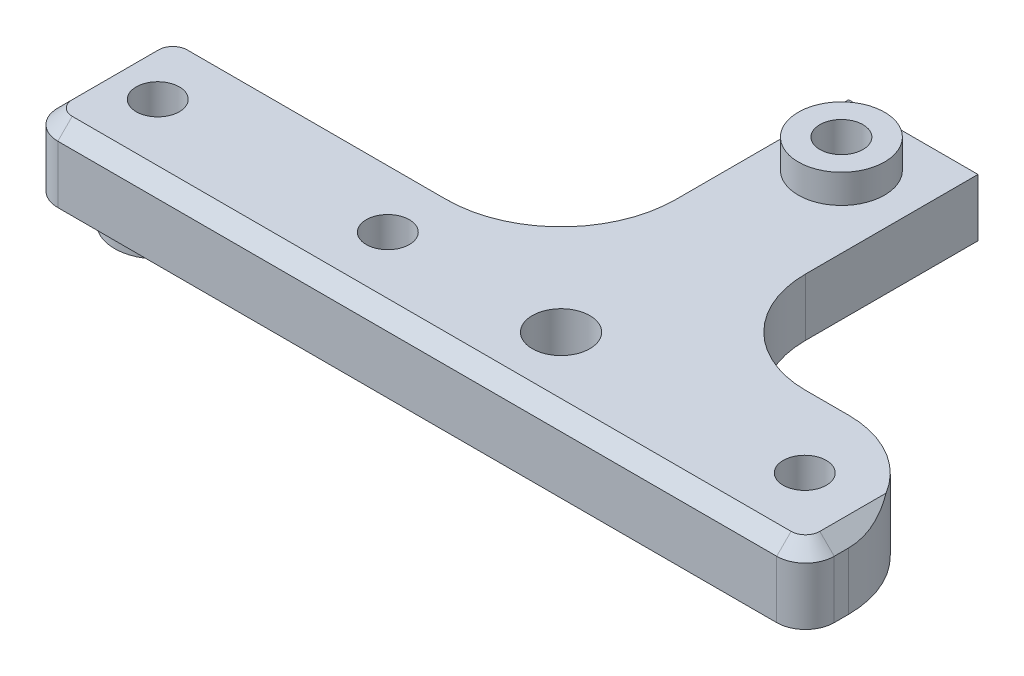
SolidWorks part; units mm, degrees
ref_plane "Front Plane" through (0, 0, 0) normal (0, 0, 1) x (1, 0, 0)
ref_plane "Top Plane" through (0, 0, 0) normal (0, 1, 0) x (1, 0, 0)
ref_plane "Right Plane" through (0, 0, 0) normal (1, 0, 0) x (0, 0, -1)
sketch "Sketch1" plane through (0, 0, 0) normal (0, 1, 0) x (1, 0, 0)
  line L1 (-27, 5) -> (27, 5)
  line L2 (-27, 5) -> (-27, -5)
  line L3 (-27, -5) -> (27, -5)
  line L4 (27, 5) -> (27, -5)
  line L5 (-27, 5) -> (27, -5) construction
  line L6 (-27, -5) -> (27, 5) construction
  point P0 (0, 0)
  dimension "D1" = 54
  dimension "D2" = 10
extrude "Boss-Extrude1" add sketch "Sketch1" along normal blind 5
sketch "Sketch3" plane through (0, 5, 0) normal (0, 1, 0) x (1, 0, 0)
  line L0 (-27, 5) -> (-27, -5) construction
  circle A0 centre (-23.05, 0) radius 1.5
  circle A1 centre (5, 0) radius 2
  circle A3 centre (-7.05, 0) radius 1.5
  circle A4 centre (21.95, 0) radius 1.5
  dimension "D3" = 3
  dimension "D4" = 4
  dimension "D7" = 3
  dimension "D9" = 3
  dimension "D1" = 28.05
  dimension "D2" = 3.95
  dimension "D8" = 16
  dimension "D10" = 29
extrude "Cut-Extrude1" cut sketch "Sketch3" against normal blind 7
fillet "Fillet1" radius 2 3 edges at (-27, 2.5, -5) (27, 2.5, 5) (-27, 2.5, 5)
sketch "Sketch4" plane through (0, 0, 0) normal (0, -1, 0) x (1, 0, 0)
  circle A0 centre (-23.05, 0) radius 1.5
  circle A1 centre (-23.05, 0) radius 3
  dimension "D1" = 1.5
extrude "Boss-Extrude2" add sketch "Sketch4" along normal blind 2.5
sketch "Sketch5" plane through (0, 0, -5) normal (0, 0, -1) x (-1, 0, 0)
  line L0 (-27, 5) -> (25, 5) construction
  line L1 (-10, 5) -> (0, 5)
  line L2 (-10, 5) -> (-10, 0)
  line L3 (-10, 0) -> (0, 0)
  line L4 (0, 5) -> (0, 0)
  line L5 (-27, 0) -> (25, 0) construction
  line L8 (27, 5) -> (27, 0) construction
  dimension "D1" = 10
  dimension "D2" = 27
extrude "Boss-Extrude3" add sketch "Sketch5" along normal blind 19
sketch "Sketch6" plane through (0, 5, 0) normal (0, 1, 0) x (1, 0, 0)
  line L0 (10, 24) -> (10, 5) construction
  line L1 (0, 24) -> (10, 24) construction
  circle A0 centre (5, 19.5) radius 1.5
  dimension "D2" = 3
  dimension "D1" = 5
  dimension "D3" = 4.5
extrude "Cut-Extrude2" cut sketch "Sketch6" against normal blind 10
sketch "Sketch7" plane through (0, 5, 0) normal (0, 1, 0) x (1, 0, 0)
  circle A0 centre (5, 19.5) radius 3
  circle A1 centre (5, 19.5) radius 1.5
  dimension "D1" = 1.5
extrude "Boss-Extrude4" add sketch "Sketch7" along normal blind 2
fillet "Fillet2" radius 7 2 edges at (0, 2.5, -5) (10, 2.5, -5)
chamfer "Chamfer1" distance 1 angle 45 12 edges at (10, 0, -18) (12.0503, 0, -7.0503) (22, 0, -5) (0, 5, -18) (-2.0503, 5, -7.0503) (-16, 5, -5) (-26.4142, 5, -4.4142) (-27, 5, 0) (-26.4142, 5, 4.4142) (0, 5, 5) (26.4142, 5, 4.4142) (27, 5, -1)
fillet "Fillet3" radius 7 1 edges at (27, 2.5, -5)
